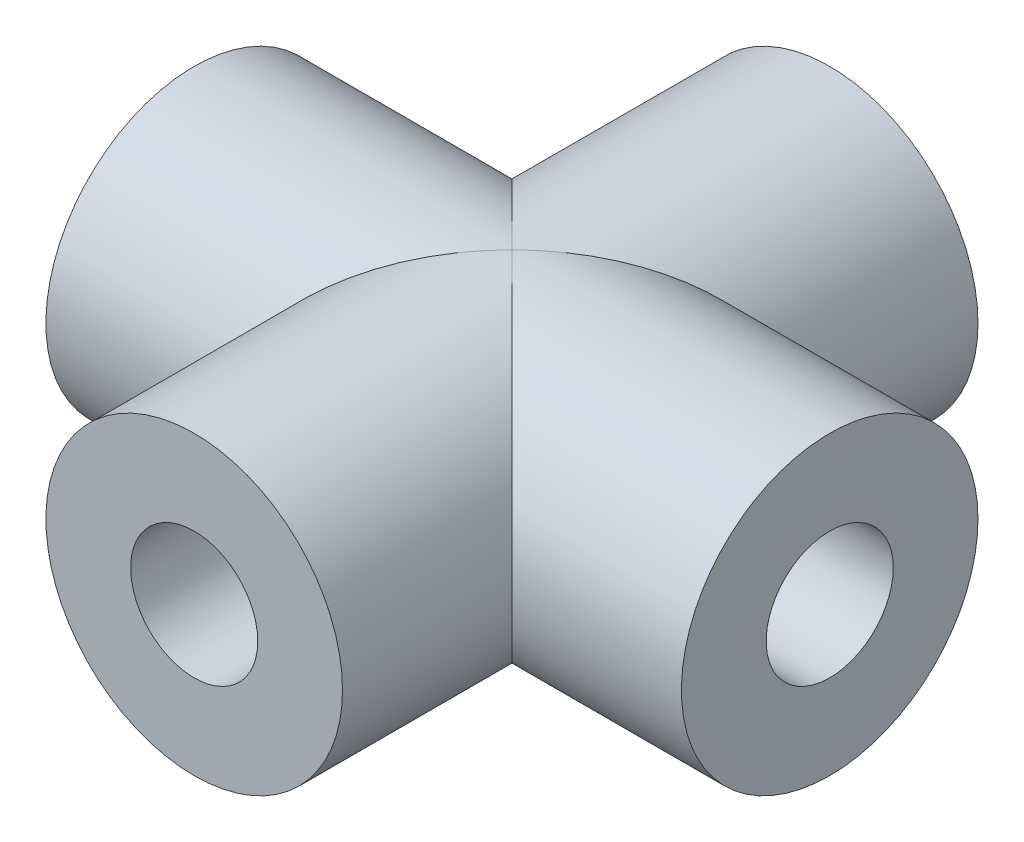
SolidWorks part; units mm, degrees
ref_plane "Front Plane" through (0, 0, 0) normal (0, 0, 1) x (1, 0, 0)
ref_plane "Top Plane" through (0, 0, 0) normal (0, 1, 0) x (1, 0, 0)
ref_plane "Right Plane" through (0, 0, 0) normal (1, 0, 0) x (0, 0, -1)
sketch "Sketch1" plane through (0, 0, 0) normal (0, 0, 1) x (1, 0, 0)
  circle A1 centre (0, 0) radius 7
  dimension "D2" = 14
extrude "Boss-Extrude1" add sketch "Sketch1" along normal mid plane 30
sketch "Sketch4" plane through (0, 0, 0) normal (1, 0, 0) x (0, 0, -1)
  line L0 (15, 7) -> (-15, 7) construction
  circle A0 centre (0, 0) radius 7
extrude "Boss-Extrude2" add sketch "Sketch4" along normal mid plane 30
sketch "Sketch3" plane through (0, 0, 15) normal (0, 0, 1) x (1, 0, 0)
  circle A0 centre (0, 0) radius 3
  dimension "D1" = 6
extrude "Cut-Extrude1" cut sketch "Sketch3" against normal blind 5.625
sketch "Sketch5" plane through (0, 0, 0) normal (0, 0, 1) x (1, 0, 0)
  line L0 (0, 7) -> (0, -7) construction
  circle A0 centre (0, 0) radius 7 construction
pattern_circular "CirPattern1" count 4 over 360 about axis through (0, 0, 0) along (0, 1, 0) of "Cut-Extrude1"
equation "\"shaft inner diameter\"= 15mm "
equation "\"shaft outer diameter\"= 20mm "
equation "\"keyway_height\" = 1.39mm "
equation "\"keyway_width\" = 2.78mm "
equation "\"keyway_length\" = 30mm "
equation "\"steering column length\" = 555mm "
equation "\"u_joint clearance\" = 30mm "
equation "\"u_joint thickness\" = 7.5mm "
equation "\"horizontal shaft length\" = 90mm "
equation "\"short_bearing_outer_width\" = 10mm "
equation "\"pinion width\" = 26.5mm "
equation "\"number of teeth\" = 18mm "
equation "\"column angle\" = 45deg "
equation "\"steering wheel bolt width\" = 6mm "
equation "\"steering wheel bolt length\" = 40mm "
equation "\"bushing length\" = 40mm "
equation "\"bushing thickness\" = 3mm "
equation "\"column bushing diameter\" = \"primary shaft small diameter\" + 4 "
equation "\"column bushing distance\" = \"steering column length\"/4 "
equation "\"D1@Cut-Extrude1\"=\"u_joint thickness\"*0.75"
equation "\"D1@Boss-Extrude1\"=\"u_joint clearance\""
equation "\"D1@Boss-Extrude2\"=\"u_joint clearance\""
equation "\"wheel base\" = 1561mm "
equation "\"track\" = 1354mm "
equation "\"turning radius\" = 2000mm "
equation "\"turn to lock\" = 0.75mm "
equation "\"steering arm length\" = 100mm "
equation "\"primary shaft small diameter\" = 16mm "
equation "\"primary shaft large diameter\" = 24mm "
equation "\"secondary shaft small diameter\" = 16mm "
equation "\"secondary shaft large diameter\" = 25mm "
equation "\"pin hole diameter\" = 10mm "
equation "\"rack hole to hole\" = 500mm "
equation "\"rack length\" = \"rack hole to hole\" + \"pin hole diameter\"*2 "
equation "\"max turning angle\" = atn(\"wheel base\" / (\"turning radius\" - 0.5 * \"track\")) "
equation "\"max travel\" = 2 * \"steering arm length\" * sin(0.5 * \"max turning angle\") "
equation "\"pitch diameter\" = \"max travel\"/(pi * \"turn to lock\") "
equation "\"pressure angle\" = 20deg "
equation "\"module\" = \"pitch diameter\" / \"number of teeth\" "
equation "\"tie rod length\" = 305mm "
equation "\"tie rod inner diameter\" = 6.6mm "
equation "\"tie rod outer diameter\" = 8.1mm "
